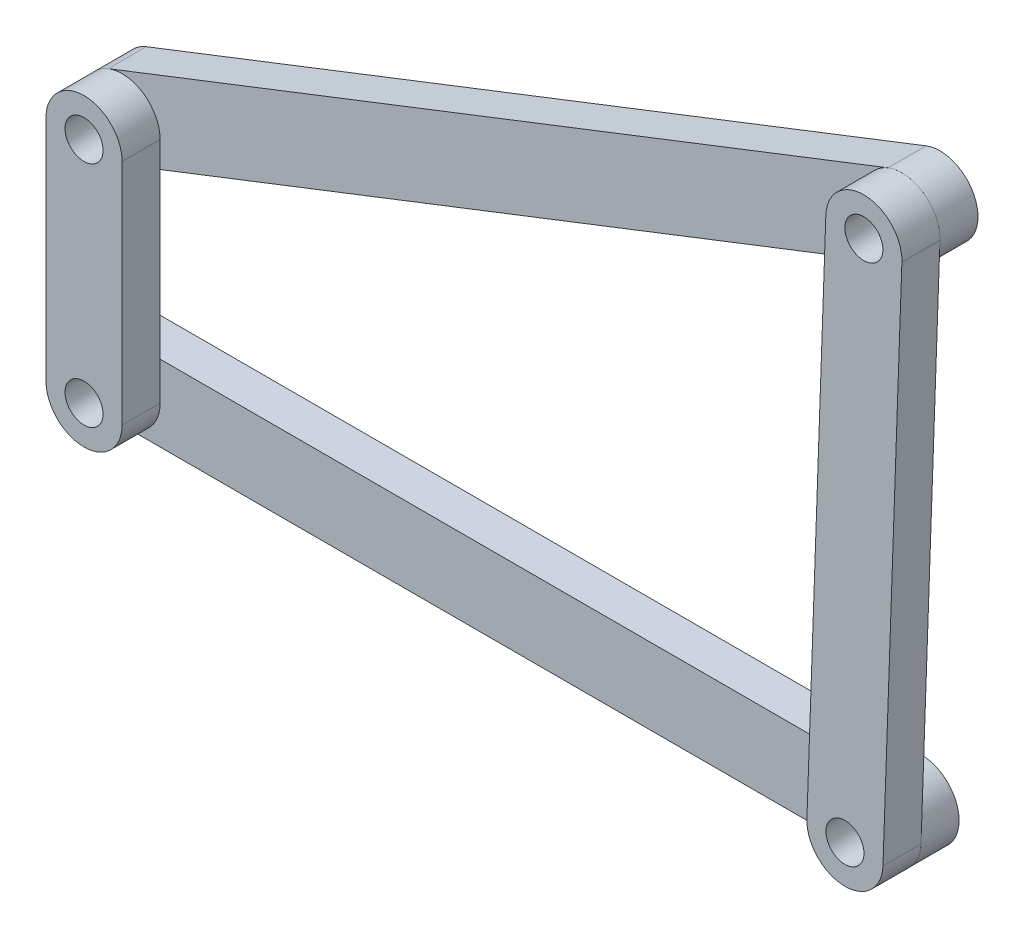
SolidWorks part; units mm, degrees
ref_plane "前视基准面" through (0, 0, 0) normal (0, 0, 1) x (1, 0, 0)
ref_plane "上视基准面" through (0, 0, 0) normal (0, 1, 0) x (1, 0, 0)
ref_plane "右视基准面" through (0, 0, 0) normal (1, 0, 0) x (0, 0, -1)
other "Configuration Table"
sketch "草图1" plane through (0, 0, 0) normal (0, 0, 1) x (1, 0, 0)
  line L0 (0, 30) -> (0, 0)
  line L1 (0, 0) -> (100, 0)
  line L2 (100, 0) -> (102.4867, 69.9558)
  line L3 (102.4867, 69.9558) -> (0, 30)
  dimension "D1" = 100
  dimension "D2" = 30
  dimension "D3" = 110
  dimension "D4" = 70
sketch "草图2" plane through (0, 0, 0) normal (0, 0, 1) x (1, 0, 0)
  line L0 (0, 0) -> (100, 0) construction
  line L1 (0, 5) -> (100, 5)
  line L2 (0, -5) -> (100, -5)
  arc A0 (0, 5) -> (0, -5) centre (0, 0) ccw
  arc A1 (100, -5) -> (100, 5) centre (100, 0) ccw
  circle A2 centre (0, 0) radius 2.5
  circle A3 centre (100, 0) radius 2.5
  point P4 (50, 0)
  dimension "D1" = 5
  dimension "D2" = 5
extrude "凸台-拉伸1" add sketch "草图2" along normal blind 5
sketch "草图3" plane through (0, 0, 5) normal (0, 0, 1) x (1, 0, 0)
  line L0 (0, 0) -> (0, 30) construction
  line L1 (-5, 0) -> (-5, 30)
  line L2 (5, 0) -> (5, 30)
  arc A0 (-5, 0) -> (5, 0) centre (0, 0) ccw
  arc A1 (5, 30) -> (-5, 30) centre (0, 30) ccw
  circle A2 centre (0, 0) radius 2.5 construction
  circle A3 centre (0, 0) radius 2.5
  circle A4 centre (0, 30) radius 2.5
  point P4 (0, 15)
  dimension "D1" = 5
extrude "凸台-拉伸2" add sketch "草图3" along normal blind 5 separate body
sketch "草图4" plane through (0, 0, 5) normal (0, 0, -1) x (-1, 0, 0)
  line L0 (0, 30) -> (-102.4867, 69.9558) construction
  line L1 (-1.8162, 25.3415) -> (-104.3029, 65.2973)
  line L2 (1.8162, 34.6585) -> (-100.6706, 74.6143)
  arc A0 (-1.8162, 25.3415) -> (1.8162, 34.6585) centre (0, 30) ccw
  arc A1 (-100.6706, 74.6143) -> (-104.3029, 65.2973) centre (-102.4867, 69.9558) ccw
  arc A2 (5, 30) -> (-5, 30) centre (0, 30) ccw construction
  circle A3 centre (0, 30) radius 2.5 construction
  circle A4 centre (0, 30) radius 2.5
  circle A5 centre (-102.4867, 69.9558) radius 2.5
  point P4 (-51.2434, 49.9779)
extrude "凸台-拉伸3" add sketch "草图4" along normal blind 5 separate body
sketch "草图5" plane through (0, 0, 5) normal (0, 0, 1) x (1, 0, 0)
  line L0 (102.4867, 69.9558) -> (100, 0) construction
  line L1 (107.4836, 69.7782) -> (104.9968, -0.1776)
  line L2 (97.4899, 70.1334) -> (95.0032, 0.1776)
  arc A0 (107.4836, 69.7782) -> (97.4899, 70.1334) centre (102.4867, 69.9558) ccw
  arc A1 (95.0032, 0.1776) -> (104.9968, -0.1776) centre (100, 0) ccw
  arc A2 (100, -5) -> (100, 5) centre (100, 0) ccw construction
  circle A3 centre (100, 0) radius 2.5 construction
  circle A4 centre (100, 0) radius 2.5
  circle A5 centre (102.4867, 69.9558) radius 2.5 construction
  circle A6 centre (102.4867, 69.9558) radius 2.5
  point P4 (101.2434, 34.9779)
extrude "凸台-拉伸4" add sketch "草图5" along normal blind 5 separate body
split "分割1" bodies to split 107 106 109 108 resulting bodies 110 111 112 113
